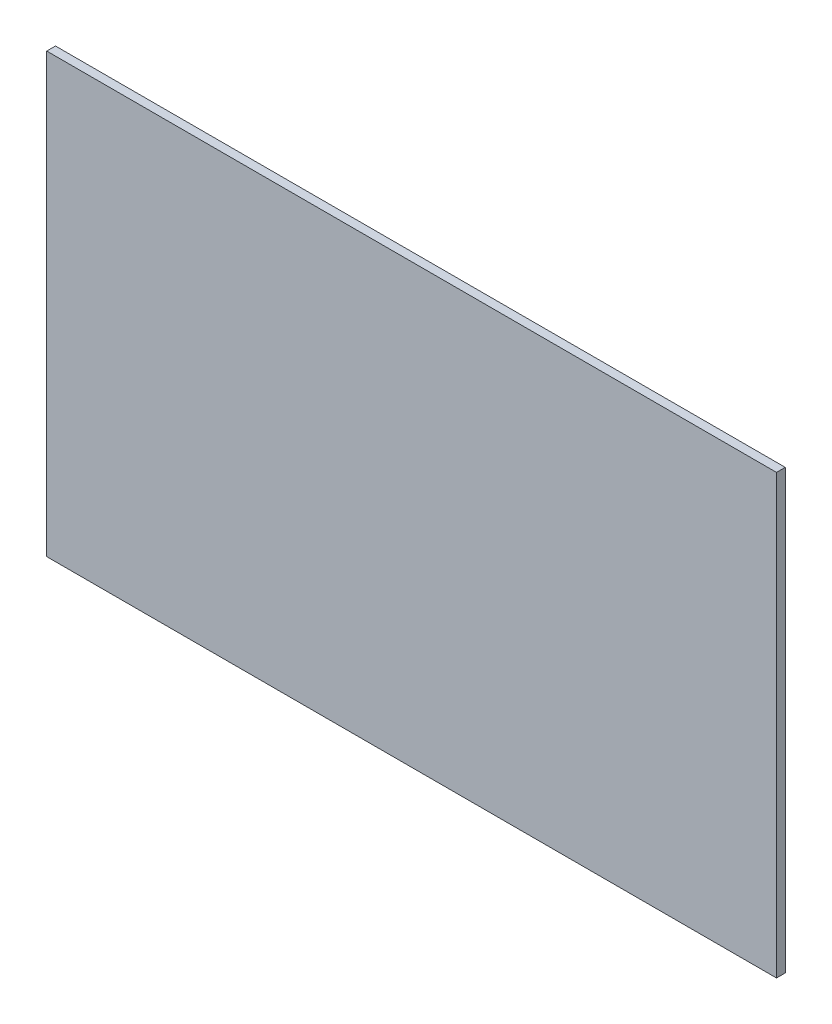
SolidWorks part; units mm, degrees
ref_plane "Front Plane" through (0, 0, 0) normal (0, 0, 1) x (1, 0, 0)
ref_plane "Top Plane" through (0, 0, 0) normal (0, 1, 0) x (1, 0, 0)
ref_plane "Right Plane" through (0, 0, 0) normal (1, 0, 0) x (0, 0, -1)
sketch "Sketch1" plane through (0, 0, 0) normal (0, 0, 1) x (1, 0, 0)
  line L1 (-63.5, -38.1) -> (63.5, -38.1)
  line L2 (-63.5, -38.1) -> (-63.5, 38.1)
  line L3 (-63.5, 38.1) -> (63.5, 38.1)
  line L4 (63.5, -38.1) -> (63.5, 38.1)
  line L5 (-63.5, -38.1) -> (63.5, 38.1) construction
  line L6 (-63.5, 38.1) -> (63.5, -38.1) construction
  point P0 (0, 0)
  dimension "D1" = 127
  dimension "D2" = 76.2
extrude "Boss-Extrude1" add sketch "Sketch1" along normal blind 1.524
